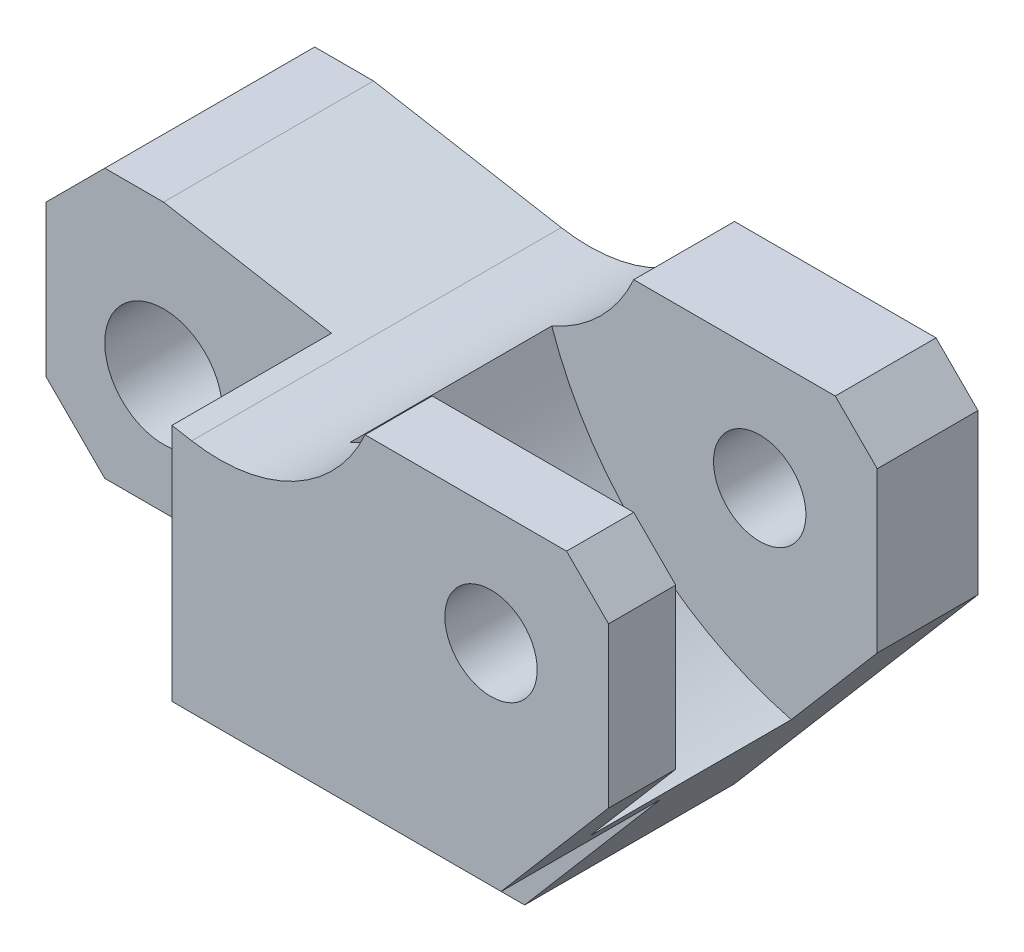
SolidWorks part; units mm, degrees
material "AISI 1020"
ref_plane "Plan de face" through (0, 0, 0) normal (0, 0, 1) x (1, 0, 0)
ref_plane "Plan de dessus" through (0, 0, 0) normal (0, 1, 0) x (1, 0, 0)
ref_plane "Plan de droite" through (0, 0, 0) normal (1, 0, 0) x (0, 0, -1)
sketch "Esquisse1" plane through (0, 0, 0) normal (0, 0, 1) x (1, 0, 0)
  line L0 (-14, 18) -> (0, 18)
  line L1 (72, -33) -> (-14, -33) construction
  line L2 (72, -33) -> (72, 25) construction
  line L3 (72, 25) -> (-14, 25) construction
  line L4 (-14, -33) -> (-14, 25) construction
  line L5 (0, 18) -> (22.3614, 14.0571)
  line L6 (43, 25) -> (67, 25)
  line L7 (67, 25) -> (72, 25)
  line L8 (72, 25) -> (72, 1)
  line L9 (72, 1) -> (43, -33)
  line L10 (43, -33) -> (37.297, -33)
  line L12 (25.5755, -14) -> (-14, -14)
  line L13 (-14, -14) -> (-14, 18)
  circle A0 centre (0, 0) radius 7
  arc A1 (22.3614, 14.0571) -> (43, 25) centre (25.6607, 32.7684) ccw
  arc A2 (37.297, -33) -> (30.5212, -18.2647) centre (59.2059, -14) cw
  arc A3 (30.5212, -18.2647) -> (25.5755, -14) centre (25.5755, -19) ccw
  circle A4 centre (58, 11) radius 5.5
  dimension "D13" = 5
  dimension "D14" = 29
  dimension "D9" = 19
  dimension "D18" = 14
  dimension "D1" = 86
  dimension "D2" = 58
  dimension "D4" = 24
  dimension "D5" = 14
  dimension "D6" = 14
  dimension "D7" = 32
  dimension "D8" = 19
  dimension "D12" = 10
  dimension "D15" = 29
  dimension "D16" = 14
  dimension "D17" = 19
  dimension "D3" = 29
  dimension "D10" = 14
  dimension "D11" = 14
extrude "Boss.-Extru.1" add sketch "Esquisse1" along normal blind 44
chamfer "Chanfrein1" distance 7 angle 45 2 edges at (-14, -14, 22) (-14, 18, 22)
chamfer "Chanfrein2" distance 5 angle 45 1 edges at (72, 25, 22)
sketch "Esquisse2" plane through (0, 25, 0) normal (0, 1, 0) x (1, 0, 0)
  line L0 (-14, -44) -> (-14, -25)
  line L1 (-14, -44) -> (-14, 0) construction
  line L2 (-14, -25) -> (20, -25)
  line L3 (20, -25) -> (20, -44)
  line L4 (22.3614, -44) -> (0, -44) construction
  line L5 (-14, -44) -> (20, -44)
  dimension "D1" = 19
  dimension "D2" = 34
extrude "Enlèv. mat.-Extru.1" cut sketch "Esquisse2" against normal through all
sketch "Esquisse4" plane through (72, 0, 0) normal (1, 0, 0) x (0, 0, -1)
  line L1 (-44, -33) -> (-25, -33)
  line L2 (-44, -33) -> (-44, -14)
  line L3 (-44, -14) -> (-25, -14)
  line L4 (-25, -33) -> (-25, -14)
  dimension "D1" = 19
  dimension "D2" = 19
extrude "Enlèv. mat.-Extru.2" cut sketch "Esquisse4" against normal through all contours L2 L1 L4 L3
sketch "Esquisse5" plane through (0, 0, 0) normal (0, 0, -1) x (-1, 0, 0)
  line L11 (-43, 25) -> (-67, 25)
  line L12 (-67, 25) -> (-72, 20)
  line L13 (-72, 20) -> (-72, 1)
  line L14 (-72, 1) -> (-43, -33)
  line L15 (-43, -33) -> (-37.297, -33)
  line L16 (-25.5755, -14) -> (7, -14)
  line L17 (7, -14) -> (14, -7)
  line L18 (14, -7) -> (14, 11)
  line L19 (14, 11) -> (7, 18)
  line L20 (7, 18) -> (0, 18)
  line L21 (0, 18) -> (-22.3614, 14.0571)
  line L22 (-43, 25) -> (-67, 25)
  line L23 (-67, 25) -> (-72, 20)
  line L24 (-72, 20) -> (-72, 1)
  line L25 (-72, 1) -> (-61.7647, -11)
  arc A0 (-61.7647, -11) -> (-33.2369, 15.3443) centre (-72, 28.7019) ccw
  arc A4 (-37.297, -33) -> (-30.5212, -18.2647) centre (-59.2059, -14) ccw
  arc A5 (-25.5755, -14) -> (-30.5212, -18.2647) centre (-25.5755, -19) ccw
  arc A6 (-43, 25) -> (-22.3614, 14.0571) centre (-25.6607, 32.7684) ccw
  arc A9 (-43, 25) -> (-33.2369, 15.3443) centre (-25.6607, 32.7684) ccw
  dimension "D2" = 41
  dimension "D3" = 36
  dimension "D1" = 0
extrude "Enlèv. mat.-Extru.3" cut sketch "Esquisse5" against normal blind 24 from offset 12 contours L22 L23 L24 L25 A0 A9
equation "\"A\"= 86"
equation "\"B\"= 58"
equation "\"C\"= 44"
equation "\"D1@Boss.-Extru.1\"=\"C\""
equation "\"D1@Esquisse1\"=\"A\""
equation "\"D2@Esquisse1\"=\"B\""
equation "\"D2@Esquisse2\"=\"A\" - 52"
